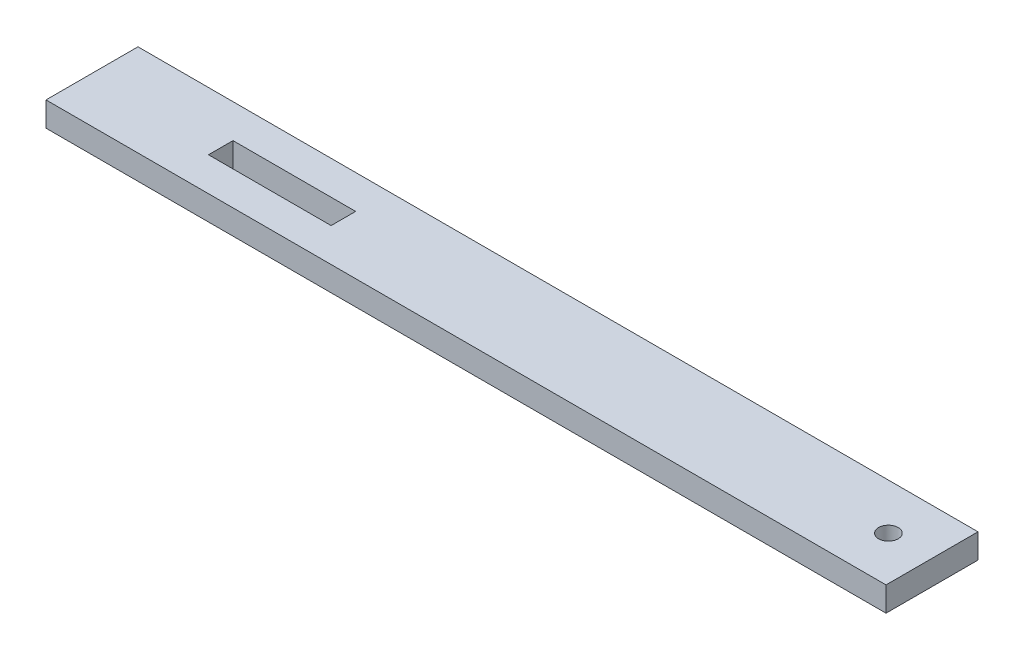
SolidWorks part; units mm, degrees
ref_plane "Front Plane" through (0, 0, 0) normal (0, 0, 1) x (1, 0, 0)
ref_plane "Top Plane" through (0, 0, 0) normal (0, 1, 0) x (1, 0, 0)
ref_plane "Right Plane" through (0, 0, 0) normal (1, 0, 0) x (0, 0, -1)
sketch "Sketch1" plane through (0, 0, 0) normal (0, 1, 0) x (1, 0, 0)
  line L1 (-39.37, -9.525) -> (39.37, -9.525)
  line L2 (-39.37, -9.525) -> (-39.37, 9.525)
  line L3 (-39.37, 9.525) -> (39.37, 9.525)
  line L4 (39.37, -9.525) -> (39.37, 9.525)
  line L5 (-39.37, -9.525) -> (39.37, 9.525) construction
  line L6 (-39.37, 9.525) -> (39.37, -9.525) construction
  point P0 (0, 0)
  dimension "D1" = 19.05
  dimension "D2" = 78.74
extrude "Boss-Extrude1" add sketch "Sketch1" along normal blind 5.08
sketch "Sketch2" plane through (0, 5.08, 0) normal (0, 1, 0) x (1, 0, 0)
  line L1 (-12.7, -2.54) -> (12.7, -2.54)
  line L2 (-12.7, -2.54) -> (-12.7, 2.54)
  line L3 (-12.7, 2.54) -> (12.7, 2.54)
  line L4 (12.7, -2.54) -> (12.7, 2.54)
  line L5 (-12.7, -2.54) -> (12.7, 2.54) construction
  line L6 (-12.7, 2.54) -> (12.7, -2.54) construction
  point P0 (0, 0)
  dimension "D1" = 5.08
  dimension "D2" = 25.4
extrude "Cut-Extrude1" cut sketch "Sketch2" against normal through all
sketch "Sketch3" plane through (39.37, 0, 0) normal (1, 0, 0) x (0, 0, -1)
  line L1 (-9.525, 0) -> (9.525, 0)
  line L2 (-9.525, 0) -> (-9.525, 5.08)
  line L3 (-9.525, 5.08) -> (9.525, 5.08)
  line L4 (9.525, 0) -> (9.525, 5.08)
extrude "Boss-Extrude2" add sketch "Sketch3" along normal blind 95.25
sketch "Sketch4" plane through (0, 0, 0) normal (0, -1, 0) x (1, 0, 0)
  line L0 (134.62, 0) -> (125.5855, 0) construction
  line L1 (134.62, 9.525) -> (134.62, -9.525) construction
  circle A0 centre (125.5855, 0) radius 2.032
  dimension "D1" = 4.064
extrude "Cut-Extrude2" cut sketch "Sketch4" against normal blind 5.08
equation "\"Foamcore\" = .1in"
equation "\"MDF\" = .2in"
equation "\"Gmaterial\"= \"MDF\""
equation "\"PVC-ID\" = \"1.590in\""
equation "\"PVC-OD\" = \"1.900in\""
equation "\"PVC-Sleeve-Width\" = \".51in\""
equation "\"D1@Sketch2\"=\"Gmaterial\""
equation "\"D1@Cut-Extrude2\"=\"Gmaterial\""
